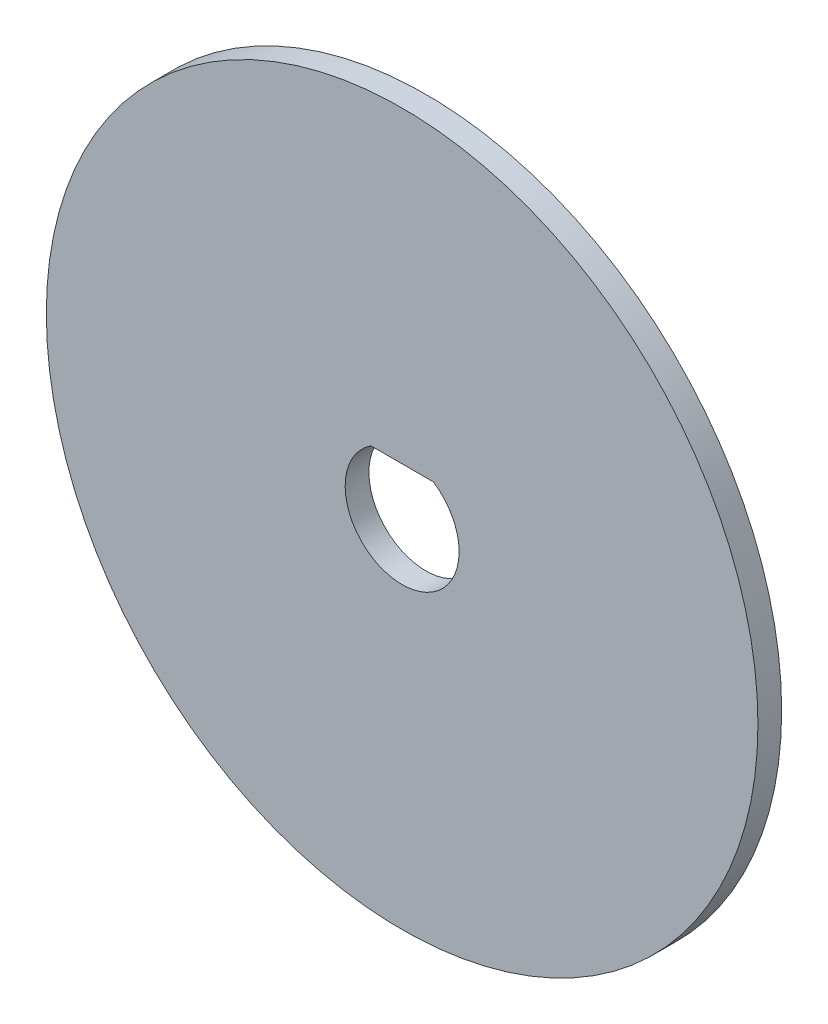
SolidWorks part; units mm, degrees
ref_plane "Front Plane" through (0, 0, 0) normal (0, 0, 1) x (1, 0, 0)
ref_plane "Top Plane" through (0, 0, 0) normal (0, 1, 0) x (1, 0, 0)
ref_plane "Right Plane" through (0, 0, 0) normal (1, 0, 0) x (0, 0, -1)
sketch "Sketch1" plane through (0, 0, 0) normal (0, 0, 1) x (1, 0, 0)
  circle A0 centre (0, 0) radius 19.05
  circle A1 centre (0, 0) radius 3.05
  dimension "D1" = 38.1
  dimension "D2" = 6.1
extrude "Boss-Extrude1" add sketch "Sketch1" along normal blind 1.27
sketch "Sketch2" plane through (0, 0, 0) normal (0, 0, -1) x (-1, 0, 0)
  line L0 (-1.524, 6.3188) -> (-1.524, 7.5888)
  line L1 (-1.524, 7.5888) -> (1.524, 7.5888)
  line L2 (1.524, 7.5888) -> (1.524, 6.3188)
  circle A0 centre (0, 0) radius 6.5
  arc A1 (-1.524, 6.3188) -> (1.524, 6.3188) centre (0, 0) cw
  point P5 (0, 7.5888)
  dimension "D1" = 13
  dimension "D2" = 1.27
  dimension "D3" = 3.048
extrude "Boss-Extrude2" add sketch "Sketch2" along normal blind 1.27 contours L2 A1 L0 L1
pattern_circular "CirPattern1" count 4 over 360 about axis through (0, 0, 0) along (0, 0, 1) of "Boss-Extrude2"
sketch "Sketch3" plane through (0, 0, 1.27) normal (0, 0, 1) x (1, 0, 0)
  line L0 (-1.6733, 2.55) -> (1.6733, 2.55)
  circle A0 centre (0, 0) radius 3.05 construction
  arc A1 (-1.6733, 2.55) -> (1.6733, 2.55) centre (0, 0) cw
  point P4 (0, -3.05)
  point P5 (0, 0.5234)
  dimension "D1" = 5.6
extrude "Boss-Extrude3" add sketch "Sketch3" against normal through all
